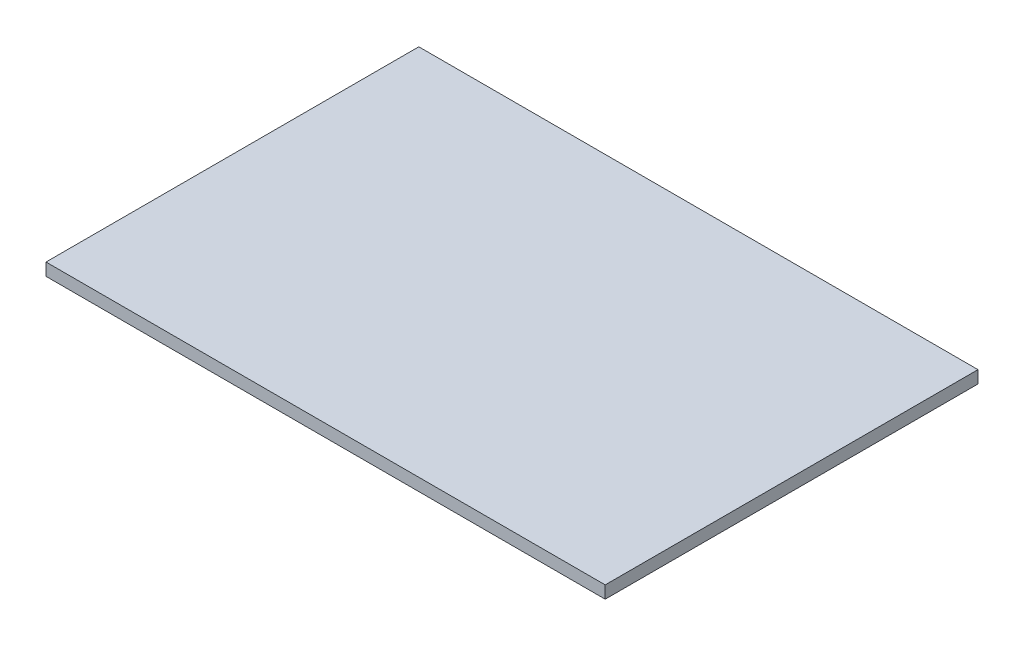
SolidWorks part; units mm, degrees
ref_plane "Front Plane" through (0, 0, 0) normal (0, 0, 1) x (1, 0, 0)
ref_plane "Top Plane" through (0, 0, 0) normal (0, 1, 0) x (1, 0, 0)
ref_plane "Right Plane" through (0, 0, 0) normal (1, 0, 0) x (0, 0, -1)
sketch "Sketch1" plane through (0, 0, 0) normal (0, 1, 0) x (1, 0, 0)
  line L1 (90, -60) -> (-90, -60)
  line L2 (90, -60) -> (90, 60)
  line L3 (90, 60) -> (-90, 60)
  line L4 (-90, -60) -> (-90, 60)
  line L5 (90, -60) -> (-90, 60) construction
  line L6 (90, 60) -> (-90, -60) construction
  point P0 (0, 0)
  dimension "D1" = 120
  dimension "D2" = 180
extrude "Boss-Extrude1" add sketch "Sketch1" along normal blind 4
